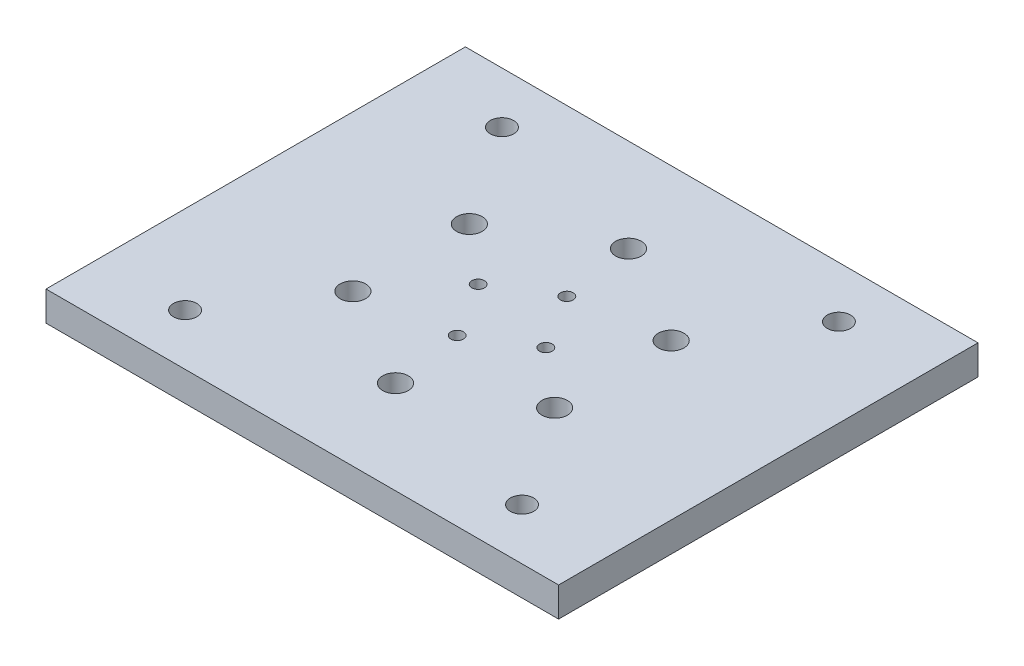
SolidWorks part; units mm, degrees
material "6061 Alloy"
ref_plane "Front Plane" through (0, 0, 0) normal (0, 0, 1) x (1, 0, 0)
ref_plane "Top Plane" through (0, 0, 0) normal (0, 1, 0) x (1, 0, 0)
ref_plane "Right Plane" through (0, 0, 0) normal (1, 0, 0) x (0, 0, -1)
sketch "Sketch2" plane through (0, 0, 0) normal (0, 1, 0) x (1, 0, 0)
  line L0 (0, 0) -> (0, 90)
  line L1 (0, 90) -> (110, 90)
  line L2 (110, 90) -> (110, 0)
  line L3 (110, 0) -> (0, 0)
  dimension "D1" = 110
  dimension "D2" = 90
extrude "Boss-Extrude1" add sketch "Sketch2" along normal blind 6.35
sketch "Sketch3" plane through (0, 6.35, 0) normal (0, 1, 0) x (1, 0, 0)
  line L1 (110, 90) -> (0, 90) construction
  line L2 (0, 0) -> (110, 0) construction
  line L4 (55, 90) -> (55, 0) construction
  line L5 (0, 45) -> (55, 45) construction
  line L6 (55, 45) -> (110, 45) construction
  line L7 (0, 90) -> (0, 0) construction
  circle A0 centre (18.85, 79) radius 2.5
  circle A1 centre (18.85, 11) radius 2.5
  circle A2 centre (91.15, 11) radius 2.5
  circle A3 centre (91.15, 79) radius 2.5
  dimension "D4" = 5
  dimension "D3" = 11
  dimension "D2" = 18.85
extrude "Mounting Holes" cut sketch "Sketch3" against normal through all
sketch "Sketch4" plane through (0, 6.35, 0) normal (0, 1, 0) x (1, 0, 0)
  line L0 (18.85, 79) -> (91.15, 11) construction
  circle A0 centre (55, 45) radius 25 construction
  circle A1 centre (55, 70) radius 2.75
  circle A2 centre (76.6506, 57.5) radius 2.75
  circle A3 centre (76.6506, 32.5) radius 2.75
  circle A4 centre (55, 20) radius 2.75
  circle A5 centre (33.3494, 32.5) radius 2.75
  circle A6 centre (33.3494, 57.5) radius 2.75
  point P20 (55, 45)
  dimension "D1" = 50
  dimension "D2" = 5.5
  dimension "D3" = 6
extrude "Cut-Extrude1" cut sketch "Sketch4" against normal up to next contours A1 | A2 | A3 | A4 | A5 | A6
sketch "Sketch5" plane through (0, 6.35, 0) normal (0, 1, 0) x (1, 0, 0)
  circle A0 centre (64.5162, 42.748) radius 1.355 construction
  circle A1 centre (45.4838, 47.252) radius 1.355 construction
  circle A2 centre (57.252, 54.5162) radius 1.355 construction
  circle A3 centre (52.748, 35.4838) radius 1.355 construction
  circle A4 centre (64.5162, 42.748) radius 1.355
  circle A5 centre (45.4838, 47.252) radius 1.355
  circle A6 centre (57.252, 54.5162) radius 1.355
  circle A7 centre (52.748, 35.4838) radius 1.355
extrude "Cut-Extrude2" cut sketch "Sketch5" against normal up to next
equation "\"L1L\"=500"
equation "\"L1Thick\"=6.35"
equation "\"Harm-Drive-Outer\"=74.5"
equation "\"L1-Spacing\"=100"
equation "\"L-Bracket-HoleToWall\"=12.5"
equation "\"D3@Sketch3\"=\"L-Bracket-HoleToSide\""
equation "\"L-Bracket-HoleToSide\"=11"
equation "\"Bracket-Hole-D\"=6.8"
equation "\"L1-Spacing\"=115.65"
equation "\"D2@Sketch3\"=\"L-Bracket-HoleToWall\"+\"L1Thick\""
